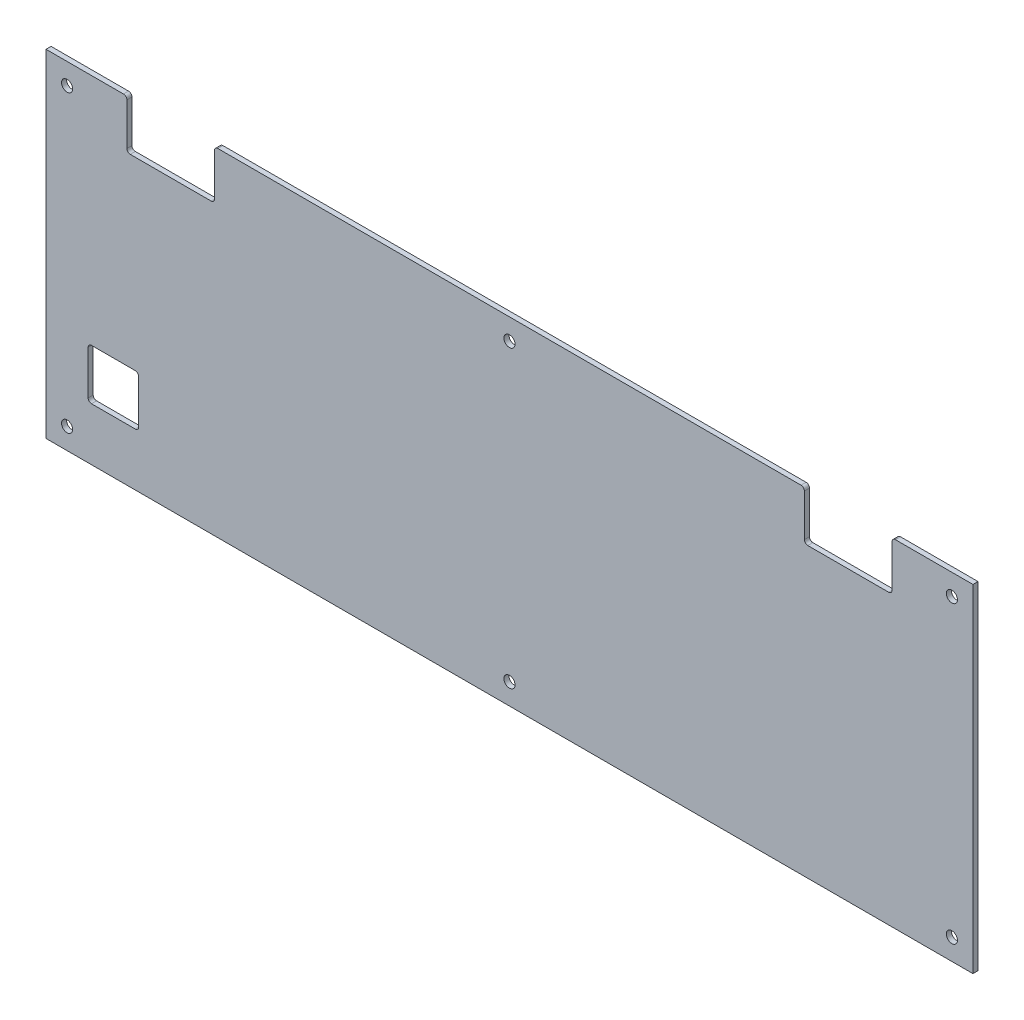
SolidWorks part; units mm, degrees
material "Acrylic (Medium-high impact)"
ref_plane "Front Plane" through (0, 0, 0) normal (0, 0, 1) x (1, 0, 0)
ref_plane "Top Plane" through (0, 0, 0) normal (0, 1, 0) x (1, 0, 0)
ref_plane "Right Plane" through (0, 0, 0) normal (1, 0, 0) x (0, 0, -1)
sketch "Sketch1" plane through (0, 0, 0) normal (0, 0, 1) x (1, 0, 0)
  line L0 (500.6453, 100) -> (500.6453, 250) construction
  line L1 (-49.3547, -25) -> (500.6453, -25)
  line L2 (-49.3547, -25) -> (-49.3547, 175)
  line L3 (-49.3547, 175) -> (-3.3547, 175)
  line L4 (500.6453, -25) -> (500.6453, 175)
  line L5 (25.6453, 175) -> (475.6453, 175) construction
  line L6 (454.6453, 175) -> (500.6453, 175)
  line L24 (452.6453, 173) -> (452.6453, 148)
  line L25 (450.6453, 146) -> (402.6453, 146)
  line L26 (400.6453, 173) -> (400.6453, 148)
  line L28 (50.6453, 173) -> (50.6453, 148)
  line L29 (48.6453, 146) -> (0.6453, 146)
  line L30 (-1.3547, 173) -> (-1.3547, 148)
  line L31 (52.6453, 175) -> (398.6453, 175)
  arc A0 (454.6453, 175) -> (452.6453, 173) centre (454.6453, 173) ccw
  arc A1 (398.6453, 175) -> (400.6453, 173) centre (398.6453, 173) cw
  arc A2 (402.6453, 146) -> (400.6453, 148) centre (402.6453, 148) cw
  arc A3 (452.6453, 148) -> (450.6453, 146) centre (450.6453, 148) cw
  arc A4 (52.6453, 175) -> (50.6453, 173) centre (52.6453, 173) ccw
  arc A5 (50.6453, 148) -> (48.6453, 146) centre (48.6453, 148) cw
  arc A6 (0.6453, 146) -> (-1.3547, 148) centre (0.6453, 148) cw
  arc A7 (-3.3547, 175) -> (-1.3547, 173) centre (-3.3547, 173) cw
  point P16 (452.6453, 175)
  point P23 (400.6453, 146)
  point P26 (452.6453, 146)
  point P29 (50.6453, 175)
  dimension "D7" = 2
  dimension "D1" = 200
  dimension "D2" = 550
  dimension "D3" = 48
  dimension "D4" = 29
  dimension "D5" = 52
  dimension "D6" = 48
extrude "Boss-Extrude1" add sketch "Sketch1" along normal blind 3
hole_wizard "M6 Clearance Hole1" positions "Sketch2" profile "Sketch3" hole size "M6" standard "ANSI Metric" end condition through all
sketch "Sketch2" plane through (0, 0, 3) normal (0, 0, 1) x (1, 0, 0)
  line L3 (-49.3547, -25) -> (500.6453, -25) construction
  line L6 (-49.3547, -25) -> (500.6453, -25) construction
  line L7 (-3.3547, 175) -> (-49.3547, 175) construction
  line L8 (-49.3547, 175) -> (-49.3547, -25) construction
  line L9 (500.6453, -25) -> (500.6453, 175) construction
  point P6 (225.6453, -12.5)
  point P16 (225.6453, 162.5)
  point P42 (225.6453, -25)
  point P50 (488.1453, -12.5)
  point P52 (488.1453, 162.5)
  point P54 (-36.8547, 162.5)
  point P56 (-36.8547, -12.5)
  dimension "D1" = 12.5
  dimension "D2" = 12.5
  dimension "D3" = 12.5
  dimension "D4" = 12.5
sketch "Sketch3" plane through (225.6453, -12.5, 3) normal (1, 0, 0) x (0, -1, 0)
  line L0 (0, 0) -> (0, 3)
  line L1 (0, 3) -> (3.3, 3)
  line L2 (3.3, 3) -> (3.3, 0)
  line L5 (3.3, 0) -> (0, 0)
  line L11 (0, -6.35) -> (0, 107.95) construction
  dimension "Thru Hole Dia." = 6.6
  dimension "Thru Hole Depth" = 3
sketch "Sketch4" plane through (0, 0, 3) normal (0, 0, 1) x (1, 0, 0)
  line L0 (-49.3547, -25) -> (500.6453, -25) construction
  line L1 (-22.3547, 6.35) -> (3.6453, 6.35)
  line L2 (-24.3547, 8.35) -> (-24.3547, 34.35)
  line L3 (-22.3547, 36.35) -> (3.6453, 36.35)
  line L4 (5.6453, 8.35) -> (5.6453, 34.35)
  line L5 (-49.3547, 175) -> (-49.3547, -25) construction
  arc A0 (-22.3547, 6.35) -> (-24.3547, 8.35) centre (-22.3547, 8.35) cw
  arc A1 (3.6453, 6.35) -> (5.6453, 8.35) centre (3.6453, 8.35) ccw
  arc A2 (3.6453, 36.35) -> (5.6453, 34.35) centre (3.6453, 34.35) cw
  arc A3 (-24.3547, 34.35) -> (-22.3547, 36.35) centre (-22.3547, 34.35) cw
  point P12 (5.6453, 6.35)
  point P15 (5.6453, 36.35)
  point P18 (-24.3547, 36.35)
  dimension "D5" = 2
  dimension "D1" = 31.35
  dimension "D2" = 25
  dimension "D3" = 30
  dimension "D4" = 30
extrude "Cut-Extrude1" cut sketch "Sketch4" against normal through all
